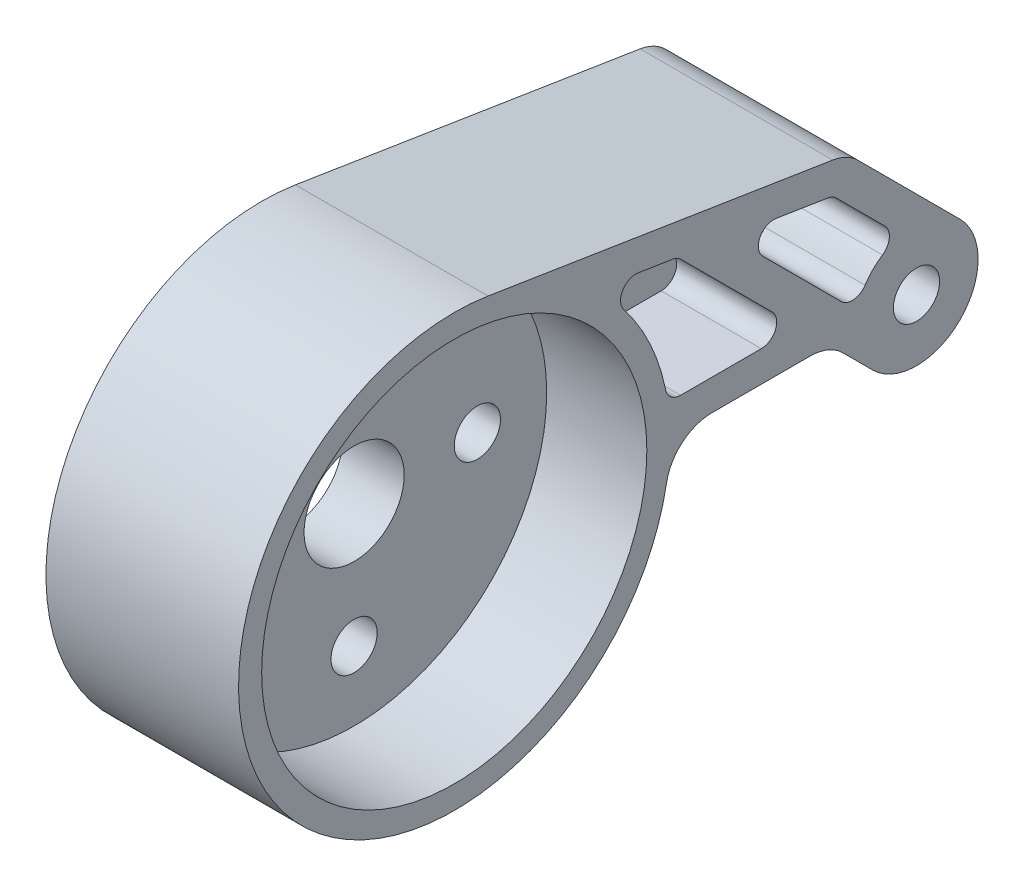
SolidWorks part; units mm, degrees
ref_plane "前视基准面" through (0, 0, 0) normal (0, 0, 1) x (1, 0, 0)
ref_plane "上视基准面" through (0, 0, 0) normal (0, 1, 0) x (1, 0, 0)
ref_plane "右视基准面" through (0, 0, 0) normal (1, 0, 0) x (0, 0, -1)
sketch "草图1" plane through (0, 0, 0) normal (1, 0, 0) x (0, 0, -1)
  line L0 (0, 0) -> (30, 0) construction
  line L3 (2.1901, 13.8276) -> (25.5251, 10.1317)
  line L4 (25.5251, 10.1317) -> (32.8284, 2.8284)
  line L5 (27.1716, -2.8284) -> (24.3431, 0)
  line L6 (24.3431, 0) -> (14, 0)
  circle A0 centre (0, 0) radius 3.25
  circle A1 centre (0, 0) radius 8 construction
  arc A2 (2.1901, 13.8276) -> (14, 0) centre (0, 0) ccw
  circle A3 centre (0, 8) radius 1.5
  circle A4 centre (8, 0) radius 1.5
  circle A5 centre (0, -8) radius 1.5
  circle A6 centre (-8, 0) radius 1.5
  circle A7 centre (30, 0) radius 1.5
  arc A8 (27.1716, -2.8284) -> (32.8284, 2.8284) centre (30, 0) ccw
  point P16 (0, 0)
  dimension "D1" = 6.5
  dimension "D2" = 16
  dimension "D3" = 28
  dimension "D4" = 3
  dimension "D6" = 3
  dimension "D7" = 8
  dimension "D8" = 30
  dimension "D9" = 45
  dimension "D10" = 45
  dimension "D11" = 9
  dimension "D5" = 4
extrude "凸台-拉伸1" add sketch "草图1" along normal blind 12.5
sketch "草图2" plane through (0, 0, 0) normal (-1, 0, 0) x (0, 0, 1)
  circle A0 centre (0, 0) radius 12.5
  dimension "D1" = 25
extrude "切除-拉伸1" cut sketch "草图2" against normal blind 2
sketch "草图3" plane through (12.5, 0, 0) normal (1, 0, 0) x (0, 0, -1)
  line L0 (14, 2) -> (13.8564, 2)
  line L16 (14, 2) -> (25.1716, 2)
  line L17 (25.1716, 2) -> (28.5858, -1.4142)
  line L18 (31.4142, 1.4142) -> (24.5704, 8.258)
  line L19 (24.5704, 8.258) -> (1.8772, 11.8523)
  line L20 (14, 2) -> (25.1716, 2)
  line L21 (25.1716, 2) -> (26.1363, 1.0353)
  line L22 (28.9647, 3.8637) -> (24.5704, 8.258)
  line L23 (24.5704, 8.258) -> (8.9995, 10.7242)
  arc A4 (28.9647, 3.8637) -> (26.1363, 1.0353) centre (30, 0) ccw
  arc A5 (28.5858, -1.4142) -> (31.4142, 1.4142) centre (30, 0) ccw
  arc A6 (13.8564, 2) -> (8.9995, 10.7242) centre (0, 0) ccw
  arc A7 (27.1716, -2.8284) -> (32.8284, 2.8284) centre (30, 0) ccw construction
  arc A8 (2.1901, 13.8276) -> (14, 0) centre (0, 0) ccw construction
  circle A9 centre (0, 0) radius 12.5
  dimension "D1" = 25
  dimension "D2" = 2
extrude "切除-拉伸2" cut sketch "草图3" against normal blind 6.5
sketch "草图4" plane through (12.5, 0, 0) normal (1, 0, 0) x (0, 0, -1)
  line L0 (25.1716, 2) -> (17.849, 9.3226)
  line L1 (24.5704, 8.258) -> (8.9995, 10.7242) construction
  line L2 (17.849, 9.3226) -> (14.4883, 9.8549)
  line L3 (14.4883, 9.8549) -> (22.3431, 2)
  line L4 (13.8564, 2) -> (25.1716, 2) construction
  line L5 (22.3431, 2) -> (25.1716, 2)
  line L7 (25.1716, 2) -> (26.1363, 1.0353) construction
  dimension "D1" = 2
extrude "凸台-拉伸2" add sketch "草图4" against normal through all
fillet "圆角1" radius 1 8 edges at (9.25, 1.0353, -26.1363) (9.25, 3.8637, -28.9647) (9.25, 8.258, -24.5704) (9.25, 9.3226, -17.849) (9.25, 2, -13.8564) (9.25, 2, -22.3431) (9.25, 9.8549, -14.4883) (9.25, 10.7242, -8.9995)
fillet "圆角2" radius 3 3 edges at (6.25, 10.1317, -25.5251) (6.25, 0, -24.3431) (6.25, 0, -14)
